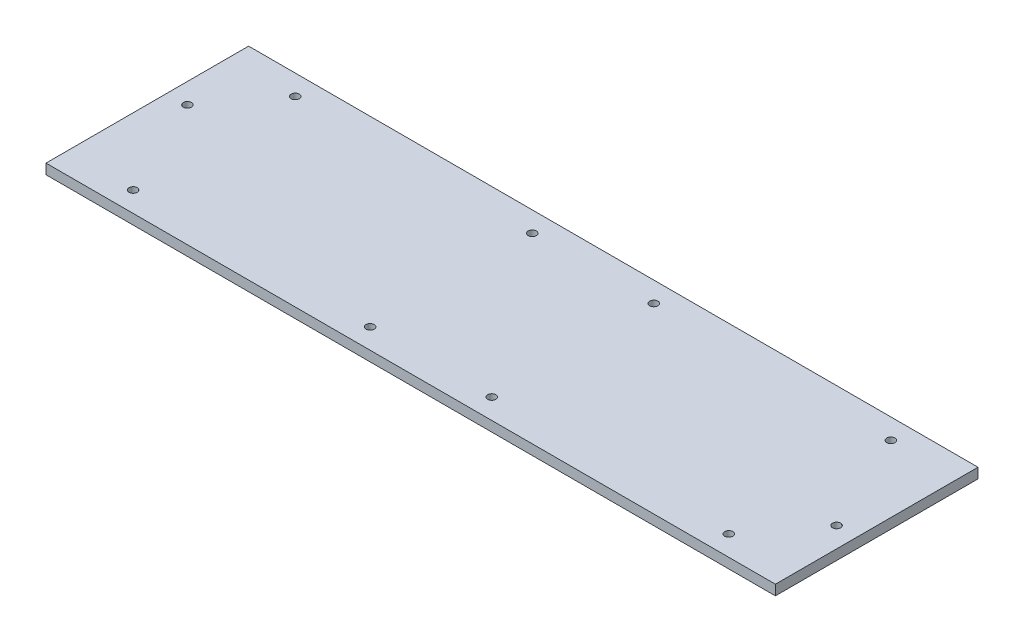
SolidWorks part; units mm, degrees
ref_plane "Front Plane" through (0, 0, 0) normal (0, 0, 1) x (1, 0, 0)
ref_plane "Top Plane" through (0, 0, 0) normal (0, 1, 0) x (1, 0, 0)
ref_plane "Right Plane" through (0, 0, 0) normal (1, 0, 0) x (0, 0, -1)
sketch "Sketch1" plane through (0, 0, 0) normal (0, 1, 0) x (1, 0, 0)
  line L0 (228.6, 127) -> (228.6, 0) construction
  line L1 (0, 0) -> (457.2, 0)
  line L2 (0, 0) -> (0, 127)
  line L3 (0, 127) -> (457.2, 127)
  line L4 (457.2, 0) -> (457.2, 127)
  line L6 (444.5, 12.7) -> (12.7, 12.7) construction
  line L7 (444.5, 12.7) -> (444.5, 114.3) construction
  line L8 (444.5, 114.3) -> (12.7, 114.3) construction
  line L9 (12.7, 12.7) -> (12.7, 114.3) construction
  line L10 (444.5, 12.7) -> (12.7, 114.3) construction
  line L11 (444.5, 114.3) -> (12.7, 12.7) construction
  circle A0 centre (41.91, 114.3) radius 2.5527
  circle A1 centre (415.29, 114.3) radius 2.5527
  circle A2 centre (415.29, 12.7) radius 2.5527
  circle A3 centre (41.91, 12.7) radius 2.5527
  circle A4 centre (190.5, 114.3) radius 2.5527
  circle A5 centre (266.7, 114.3) radius 2.5527
  circle A6 centre (190.5, 12.7) radius 2.5527
  circle A8 centre (266.7, 12.7) radius 2.5527
  circle A9 centre (444.5, 51.054) radius 2.5527
  circle A11 centre (12.7, 75.946) radius 2.5527
  point P7 (228.6, 63.5)
  dimension "D5" = 5.1054
  dimension "D6" = 190.5
  dimension "D7" = 41.91
  dimension "D8" = 5.1054
  dimension "D9" = 190.5
  dimension "D10" = 41.91
  dimension "D11" = 190.5
  dimension "D13" = 5.1054
  dimension "D15" = 5.1054
  dimension "D18" = 5.1054
  dimension "D19" = 190.5
  dimension "D21" = 5.1054
  dimension "D23" = 5.1054
  dimension "D20" = 5.1054
  dimension "D24" = 5.1054
  dimension "D25" = 5.1054
  dimension "D1" = 457.2
  dimension "D2" = 127
  dimension "D3" = 12.7
  dimension "D4" = 12.7
  dimension "D14" = 41.91
  dimension "D16" = 41.91
  dimension "D17" = 51.054
  dimension "D22" = 51.054
extrude "Boss-Extrude1" add sketch "Sketch1" along normal blind 6.35
